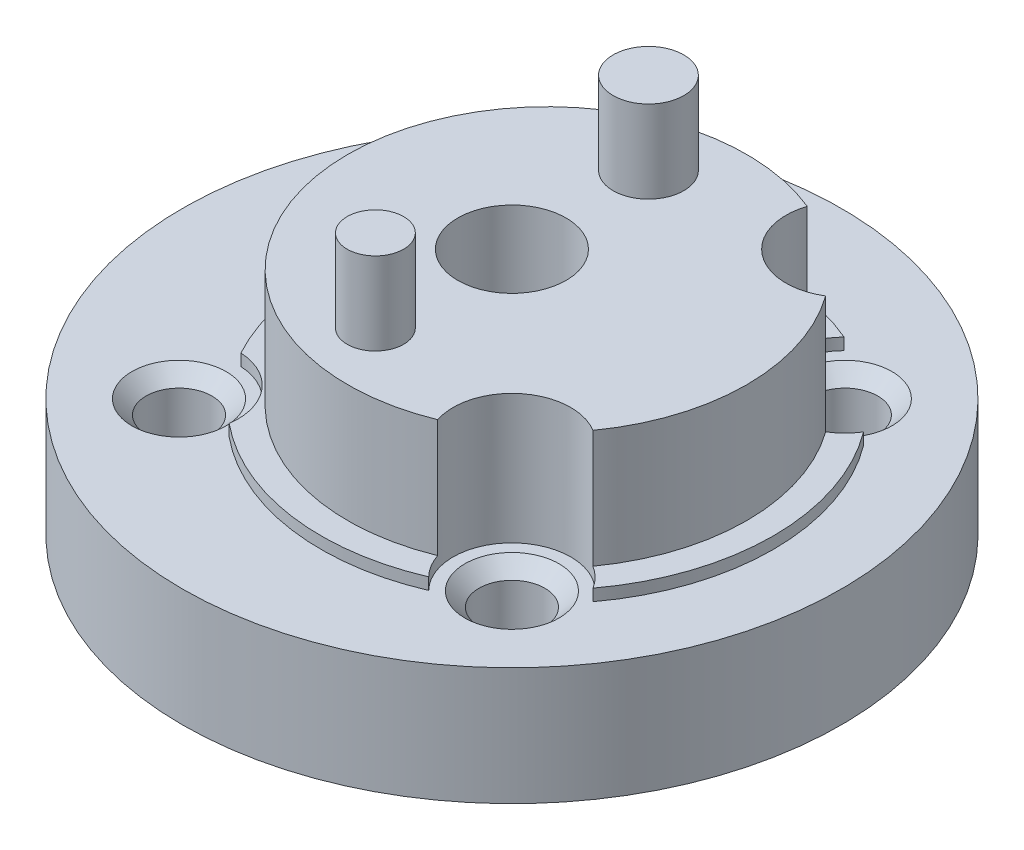
SolidWorks part; units mm, degrees
ref_plane "Front Plane" through (0, 0, 0) normal (0, 0, 1) x (1, 0, 0)
ref_plane "Top Plane" through (0, 0, 0) normal (0, 1, 0) x (1, 0, 0)
ref_plane "Right Plane" through (0, 0, 0) normal (1, 0, 0) x (0, 0, -1)
sketch "Sketch1" plane through (0, 0, 0) normal (0, 1, 0) x (1, 0, 0)
  circle A0 centre (0, 0) radius 14
  dimension "D1" = 28
extrude "Boss-Extrude1" add sketch "Sketch1" along normal blind 5
sketch "Sketch2" plane through (0, 5, 0) normal (0, 1, 0) x (1, 0, 0)
  line L0 (-2.75, 0) -> (2.75, 0) construction
  circle A0 centre (1.5, 0) radius 9.6
  dimension "D1" = 19.2
  dimension "D2" = 1.5
extrude "Boss-Extrude2" add sketch "Sketch2" along normal blind 0.5
sketch "Sketch3" plane through (0, 5.5, 0) normal (0, 1, 0) x (1, 0, 0)
  circle A0 centre (1.5, 0) radius 8.475
  dimension "D1" = 16.95
extrude "Boss-Extrude3" add sketch "Sketch3" along normal blind 5
sketch "Sketch4" plane through (0, 5, 0) normal (0, 1, 0) x (1, 0, 0)
  line L0 (-0.1258, 0) -> (-17.3037, 0) construction
  line L1 (-5.775, 0) -> (5.775, 0) construction
  line L2 (0, 0) -> (-7.0711, 7.0711) construction
  circle A0 centre (-7.0711, 7.0711) radius 1.4
  dimension "D1" = 2.8
  dimension "D2" = 45
  dimension "D3" = 10
extrude "Cut-Extrude1" cut sketch "Sketch4" against normal through all
pattern_circular "CirPattern1" count 4 over 360 about axis through (0, 0, 0) along (0, 1, 0) of "Cut-Extrude1"
sketch "Sketch5" plane through (0, 5, 0) normal (0, 1, 0) x (1, 0, 0)
  circle A0 centre (-7.0711, 7.0711) radius 2.5
  circle A1 centre (7.0711, 7.0711) radius 2.5
  circle A2 centre (7.0711, -7.0711) radius 2.5
  circle A3 centre (-7.0711, -7.0711) radius 2.5
  point P12 (0, 0)
  dimension "D1" = 5
  dimension "D2" = 4
extrude "Cut-Extrude2" cut sketch "Sketch5" along normal through all
chamfer "Chamfer1" distance 0.6 angle 45 4 edges at (-5.6711, 5, 7.0711) (7.0711, 5, 5.6711) (5.6711, 5, -7.0711) (-7.0711, 5, -5.6711)
sketch "Sketch6" plane through (0, 0, 0) normal (0, -1, 0) x (1, 0, 0)
  circle A0 centre (0, 0) radius 4.25
  dimension "D1" = 8.5
extrude "Cut-Extrude3" cut sketch "Sketch6" against normal blind 2.5
sketch "Sketch7" plane through (0, 10.5, 0) normal (0, 1, 0) x (1, 0, 0)
  circle A0 centre (0, 0) radius 2.3
  dimension "D1" = 4.6
extrude "Cut-Extrude4" cut sketch "Sketch7" against normal blind 6.5
sketch "Sketch8" plane through (0, 10.5, 0) normal (0, 1, 0) x (1, 0, 0)
  line L0 (0, -5.775) -> (0, 5.775) construction
  circle A0 centre (0, 5.8) radius 1.5
  circle A2 centre (0, -5.8) radius 1.2
  dimension "D1" = 3
  dimension "D4" = 2.4
  dimension "D2" = 5.8
  dimension "D3" = 5.8
extrude "Boss-Extrude4" add sketch "Sketch8" along normal blind 3.5
equation "\"pin_circle_R\" = 27"
equation "\"ecc\" = 1.5"
equation "\"n_pins\" = 11"
equation "\"pin_d\" = 3"
equation "\"out_pin_R\" = 18.5"
equation "\"disc_clr\" = 0.1"
equation "\"seat_6803\" = 26.1"
equation "\"disc_t\" = 5"
equation "\"out_hole_clr\" = 0.2"
equation "\"boss_17\" = 16.95"
equation "\"rotor_bolt_R\" = 10"
equation "\"m25_clr\" = 2.8"
equation "\"m25_head\" = 5"
equation "\"insert_hole\" = 4.6"
equation "\"D2@Sketch2\"=\"ecc\""
equation "\"D1@Sketch3\"=\"boss_17\""
equation "\"D1@Sketch4\"=\"m25_clr\""
equation "\"D3@Sketch4\"=\"rotor_bolt_R\""
equation "\"csk\" = 0.6"
equation "\"peg_d\" = 3.0"
equation "\"D1@Sketch5\"=\"m25_head\""
equation "\"D1@Chamfer1\"=\"csk\""
equation "\"D1@Sketch7\"=\"insert_hole\""
equation "\"D1@Sketch8\"=\"peg_d\""
equation "\"D4@Sketch8\"=\"peg_d\" - 0.6"
